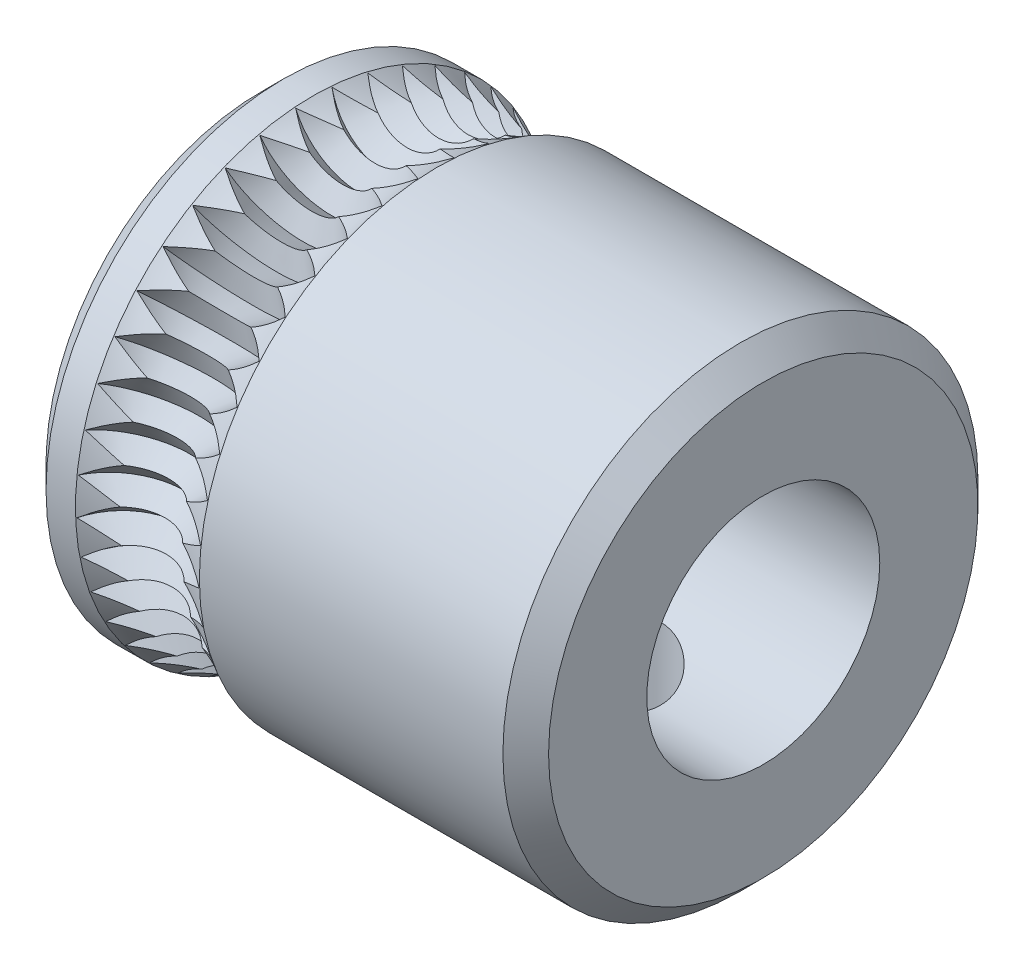
SolidWorks part; units mm, degrees
material "6061-T6 (SS)"
ref_plane "Front Plane" through (0, 0, 0) normal (0, 0, 1) x (1, 0, 0)
ref_plane "Top Plane" through (0, 0, 0) normal (0, 1, 0) x (1, 0, 0)
ref_plane "Right Plane" through (0, 0, 0) normal (1, 0, 0) x (0, 0, -1)
sketch "Sketch1" plane through (0, 0, 0) normal (0, 1, 0) x (1, 0, 0)
  line L0 (0, 0) -> (103.3356, 0) construction
  line L1 (-55, 0) -> (55, 0) construction
  line L2 (8.5, 0) -> (8.5, 5.2)
  line L5 (8.5, 5.2) -> (-2.5, 5.2)
  line L6 (-2.5, 5.2) -> (-2.5, 0)
  line L9 (-2.5, 0) -> (8.5, 0)
  line L10 (0, 0) -> (0, 50.0568) construction
  line L11 (0, -55) -> (0, 55) construction
  dimension "D1" = 5
  dimension "D2" = 10.4
  dimension "D3" = 8.5
  dimension "D5" = 11
revolve "Revolve1" add sketch "Sketch1" angle 360 about L0
sketch "Sketch3" plane through (8.5, 0, 0) normal (1, 0, 0) x (0, 0, -1)
  circle A0 centre (0, 0) radius 2.55
  dimension "D1" = 5.1
extrude "Cut-Extrude2" cut sketch "Sketch3" against normal through all
sketch "Sketch6" plane through (0, 0, 0) normal (0, 0, 1) x (1, 0, 0)
  line L2 (0, 0) -> (8.5, 0) construction
  line L3 (8.5, -2.55) -> (8.5, 2.55) construction
  line L4 (2.019, 4.8) -> (50002.019, 4.8) construction
  circle A0 centre (0, 7.3) radius 2.5
  dimension "D1" = 5
  dimension "D2" = 4.8
revolve "Cut-Revolve1" cut sketch "Sketch6" angle 360 about L2
sketch "Sketch7" plane through (0, 0, 0) normal (0, 1, 0) x (1, 0, 0)
  line L0 (-5.7773, 0) -> (5.7773, 0) construction
  line L1 (0, -5.7773) -> (0, 5.7773) construction
  circle A0 centre (5, 0) radius 1.25
  dimension "D1" = 2.5
  dimension "D2" = 5
extrude "Cut-Extrude3" cut sketch "Sketch7" against normal through all
sketch "Sketch8" plane through (0, 0, 0) normal (1, 0, 0) x (0, 0, -1)
  line L0 (0, -5.2) -> (1.4042, -5.2) construction
  line L1 (0, 5.72) -> (0, -5.72) construction
  line L2 (-0.5236, -4.7714) -> (0, -4.2)
  line L3 (0, -4.2) -> (0.5236, -4.7714)
  line L4 (0.5236, -5.6) -> (1.4395, -5.6) construction
  line L5 (-4.6276, -4.7714) -> (3.9424, -4.7714) construction
  line L6 (-0.5236, -4.7714) -> (-0.5236, -5.6)
  line L7 (-0.5236, -5.6) -> (0.5236, -5.6)
  line L8 (0.5236, -4.7714) -> (0.5236, -5.6)
  line L9 (0, 4.7714) -> (0, -4.7714) construction
  line L10 (0, 9.8) -> (0, 4.8) construction
  line L11 (5.72, 0) -> (-5.72, 0) construction
  circle A0 centre (0, 0) radius 4.8 construction
  circle A2 centre (0, 0) radius 5.2 construction
  dimension "D1" = 85
  dimension "D2" = 1
  dimension "D3" = 0.4
  dimension "D4" = 4.2
revolve "Cut-Revolve4" cut sketch "Sketch8" angle 360 about L4
pattern_circular "CirPattern1" count 41 over 360 about axis through (-2.5, 0, 0) along (1, 0, 0) of "Cut-Revolve4"
chamfer "Chamfer1" distance 0.5 angle 45 2 edges at (8.5, 0, 5.2) (-2.5, 0, 5.2)
